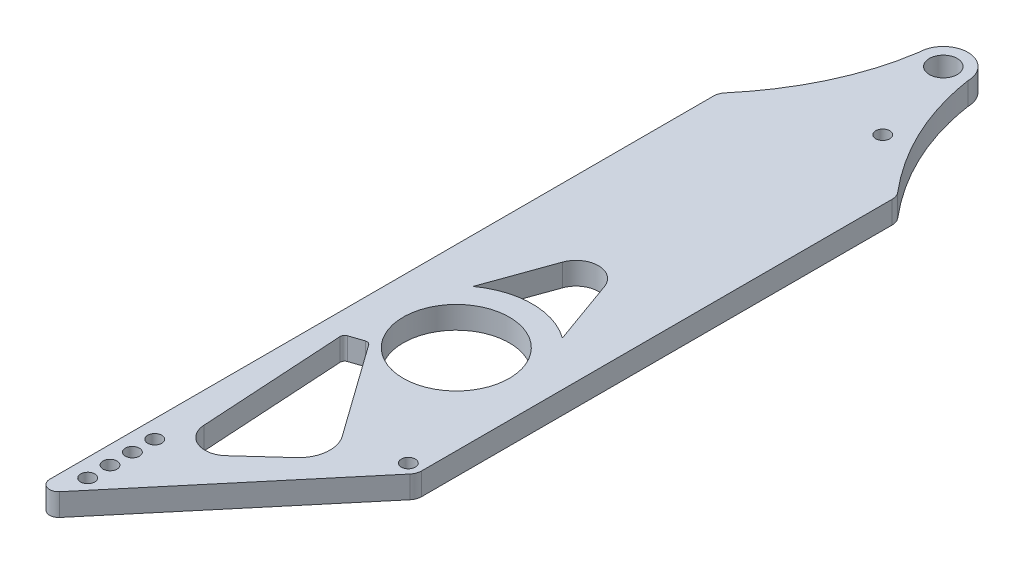
SolidWorks part; units mm, degrees
material "6061-T6 (SS)"
ref_plane "X-Y Datum" through (0, 0, 0) normal (0, 0, 1) x (1, 0, 0)
ref_plane "X-Z Datum" through (0, 0, 0) normal (0, 1, 0) x (1, 0, 0)
ref_plane "Y-Z Datum" through (0, 0, 0) normal (1, 0, 0) x (0, 0, -1)
other "Graphic1" [suppressed]
other "Graphic (Closed) -1" [suppressed]
sketch "Sketch1" plane through (0, 0, 0) normal (0, 1, 0) x (1, 0, 0)
  line L0 (25.4, -39.9268) -> (25.4, -173.6508)
  line L2 (-25.4, -228.6) -> (-25.4, -39.9268)
  line L6 (25.4, -138.43) -> (-25.4, -138.43) construction
  line L9 (24.5086, -176.0998) -> (-20.9142, -230.2327)
  line L11 (5.6055, -176.4523) -> (-13.1669, -150.1549)
  line L13 (4.3503, -188.1952) -> (-6.1618, -197.7524)
  line L14 (-16.7719, -193.4369) -> (-19.261, -152.2369)
  line L15 (-18.3959, -150.9558) -> (-14.6031, -149.6883)
  line L16 (4.5321, -177.1905) -> (-7.7137, -164.3148) construction
  line L18 (14.9571, -159.6762) -> (8.7527, -176.3269) construction
  line L20 (-12.7, -120.9704) -> (-5.9766, -102.2413)
  line L21 (5.9766, -102.2413) -> (12.7, -120.9704)
  line L22 (-3.3709, -16.2433) -> (-14.5081, -37.3849) construction
  line L23 (-15.24, -40.3445) -> (-15.24, -68.2845) construction
  line L24 (-8.6044, -70.0625) -> (-1.0999, -57.0642) construction
  line L25 (1.0999, -57.0642) -> (8.6044, -70.0625) construction
  line L26 (15.24, -68.2845) -> (15.24, -40.3445) construction
  line L27 (14.5081, -37.3849) -> (3.3709, -16.2433) construction
  line L28 (8.89, -40.3445) -> (-8.89, -40.3445) construction
  line L29 (15.24, -55.1592) -> (-15.24, -55.1592) construction
  circle A0 centre (0, 0) radius 3.9688
  circle A2 centre (0, -138.43) radius 15.0813
  circle A6 centre (-20.32, -222.8786) radius 2
  circle A7 centre (-20.32, -216.5286) radius 2
  circle A8 centre (-20.32, -210.1786) radius 2
  circle A9 centre (-20.32, -203.8286) radius 2
  arc A10 (6.985, 0) -> (-6.985, 0) centre (0, 0) ccw
  arc A11 (-16.7719, -193.4369) -> (-6.1618, -197.7524) centre (-10.4335, -193.054) ccw
  arc A12 (-18.3959, -150.9558) -> (-19.261, -152.2369) centre (-17.9933, -152.1603) ccw
  arc A13 (-14.6031, -149.6883) -> (-13.1669, -150.1549) centre (-14.2005, -150.8928) cw
  arc A14 (4.3503, -188.1952) -> (5.6055, -176.4523) centre (-1.6301, -181.6174) ccw
  arc A16 (13.5694, -155.2229) -> (14.9571, -159.6762) centre (11.3869, -158.3458) cw construction
  arc A17 (4.5321, -177.1905) -> (8.7527, -176.3269) centre (6.3726, -175.4401) ccw construction
  arc A21 (-3.3709, -16.2433) -> (3.3709, -16.2433) centre (0, -18.0191) cw construction
  arc A25 (14.5081, -37.3849) -> (15.24, -40.3445) centre (8.89, -40.3445) cw construction
  arc A26 (-14.5081, -37.3849) -> (-15.24, -40.3445) centre (-8.89, -40.3445) ccw construction
  arc A27 (13.5694, -155.2229) -> (-7.3523, -158.7295) centre (0, -138.43) cw construction
  arc A28 (-7.3523, -158.7295) -> (-7.7137, -164.3148) centre (-4.953, -161.6891) ccw construction
  arc A29 (-15.24, -68.2845) -> (-8.6044, -70.0625) centre (-11.684, -68.2845) ccw construction
  arc A30 (8.6044, -70.0625) -> (15.24, -68.2845) centre (11.684, -68.2845) ccw construction
  arc A31 (-1.0999, -57.0642) -> (1.0999, -57.0642) centre (0, -57.6992) cw construction
  arc A32 (12.7, -120.9704) -> (-12.7, -120.9704) centre (0, -138.43) ccw
  arc A33 (-5.9766, -102.2413) -> (5.9766, -102.2413) centre (0, -104.3868) cw
  arc A34 (24.5041, -37.4724) -> (25.4, -39.9268) centre (21.59, -39.9268) cw
  arc A35 (-24.5041, -37.4724) -> (-25.4, -39.9268) centre (-21.59, -39.9268) ccw
  arc A36 (25.4, -173.6508) -> (24.5086, -176.0998) centre (21.59, -173.6508) cw
  arc A37 (-25.4, -228.6) -> (-20.9142, -230.2327) centre (-22.86, -228.6) ccw
  circle A38 centre (21.59, -39.9268) radius 1.5875 construction
  circle A39 centre (21.59, -173.6508) radius 2
  circle A40 centre (10.668, -22.86) radius 2 construction
  circle A41 centre (8.1946, -25.4) radius 2
  spline S0 degree 3 poles (24.5041, -37.4724) (15.363, -26.6191) (9.1782, -14.2) (6.985, 0) knots 0.031766 0.031766 0.031766 0.031766 1 1 1 1
  spline S1 degree 3 poles (-24.5041, -37.4724) (-15.3415, -26.5935) (-9.1434, -14.1045) (-6.985, 0) knots 0.031078 0.031078 0.031078 0.031078 1 1 1 1
  point P44 (0, -55.1592)
  point P58 (0, -40.3445)
  point P66 (25.4, -175.0375)
  point P68 (-15.24, -81.5557)
  point P71 (15.24, -81.5557)
  point P75 (15.24, -38.7742)
  point P78 (-15.24, -38.7742)
  point P80 (-25.4, -235.5786)
  point P85 (-15.24, -81.5557)
  point P88 (15.24, -81.5557)
  point P92 (0, -55.1592)
  dimension "D1" = 7.9375
  dimension "D4" = 30.1625
  dimension "D8" = 4
  dimension "D6" = 6.985
  dimension "D18" = 6.35
  dimension "D19" = 1.27
  dimension "D20" = 1.27
  dimension "D21" = 8.89
  dimension "D28" = 3.81
  dimension "D29" = 2.54
  dimension "D32" = 3.81
  dimension "D33" = 6.35
  dimension "D37" = 21.59
  dimension "D41" = 3.81
  dimension "D46" = 3.556
  dimension "D47" = 1.27
  dimension "D49" = 21.59
  dimension "D31" = 6.35
  dimension "D17" = 3.81
  dimension "D52" = 3.81
  dimension "D55" = 3.81
  dimension "D56" = 2.54
  dimension "D43" = 22.352
  dimension "D44" = 22.352
  dimension "D53" = 3.175
  dimension "D54" = 4
  dimension "D62" = 4
  dimension "D65" = 4
  dimension "D3" = 138.43
  dimension "D9" = 5.08
  dimension "D10" = 12.7
  dimension "D11" = 6.35
  dimension "D12" = 6.35
  dimension "D13" = 6.35
  dimension "D5" = 50.8
  dimension "D7" = 140
  dimension "D14" = 19.05
  dimension "D16" = 12.7
  dimension "D22" = 18.0165
  dimension "D23" = 6.5799
  dimension "D24" = 107.042
  dimension "D25" = 105.022
  dimension "D26" = 3.999
  dimension "D34" = 32.3103
  dimension "D35" = 41.2751
  dimension "D36" = 27.8194
  dimension "D38" = 21.2136
  dimension "D39" = 16.7929
  dimension "D27" = 64
  dimension "D40" = 4.6645
  dimension "D42" = 5.597
  dimension "D45" = 60
  dimension "D48" = 27.94
  dimension "D30" = 25.4
  dimension "D50" = 30.48
  dimension "D51" = 19.8993
  dimension "D57" = 24.5041
  dimension "D58" = 37.4724
  dimension "D59" = 40.3445
  dimension "D60" = 18.0191
  dimension "D15" = 25.4
  dimension "D61" = 228.6
  dimension "D63" = 22.86
  dimension "D64" = 10.668
  dimension "D66" = 25.4
extrude "Boss-Extrude1" add sketch "Sketch1" against normal blind 6.35
sketch "Sketch4" plane through (0, 0, 0) normal (0, 1, 0) x (1, 0, 0)
  line L0 (0, -34.29) -> (0, 0)
  line L1 (0, 0) -> (152.4, 0)
  line L2 (152.4, 0) -> (0, -34.29)
  line L3 (0, 0) -> (7.3435, -32.6377) construction
  dimension "D1" = 12.68
  dimension "D2" = 156.21
  dimension "D3" = 34.29
  dimension "D4" = 152.4
  dimension "D5" = 33.4537
sketch "Sketch8" plane through (-25.4, 0, 0) normal (-1, 0, 0) x (0, 0, 1)
  line L0 (197.4786, 0) -> (197.4786, -6.35)
  line L1 (39.9268, 0) -> (228.6, 0) construction
  line L2 (39.9268, -6.35) -> (228.6, -6.35) construction
  line L4 (235.5786, -6.35) -> (235.5786, 0) construction
  dimension "D1" = 38.1
split line "Split Line1"
sketch "Sketch9" plane through (0, 0, 0) normal (0, 1, 0) x (1, 0, 0)
  line L0 (0, 0) -> (0, -153.8485)
  line L1 (0, -153.8485) -> (38.1, 0)
  line L2 (38.1, 0) -> (0, 0)
  line L3 (0, 0) -> (35.8984, -8.8901) construction
  dimension "D1" = 158.496
  dimension "D2" = 0
  dimension "D3" = 38.1
  dimension "D4" = 36.9828
  dimension "D5" = 76.091
equation "\"toePadMount\"=0.25"
equation "\"D11@Sketch1\"=\"toePadMount\""
equation "\"D12@Sketch1\"=\"toePadMount\""
equation "\"D13@Sketch1\"=\"toePadMount\""
